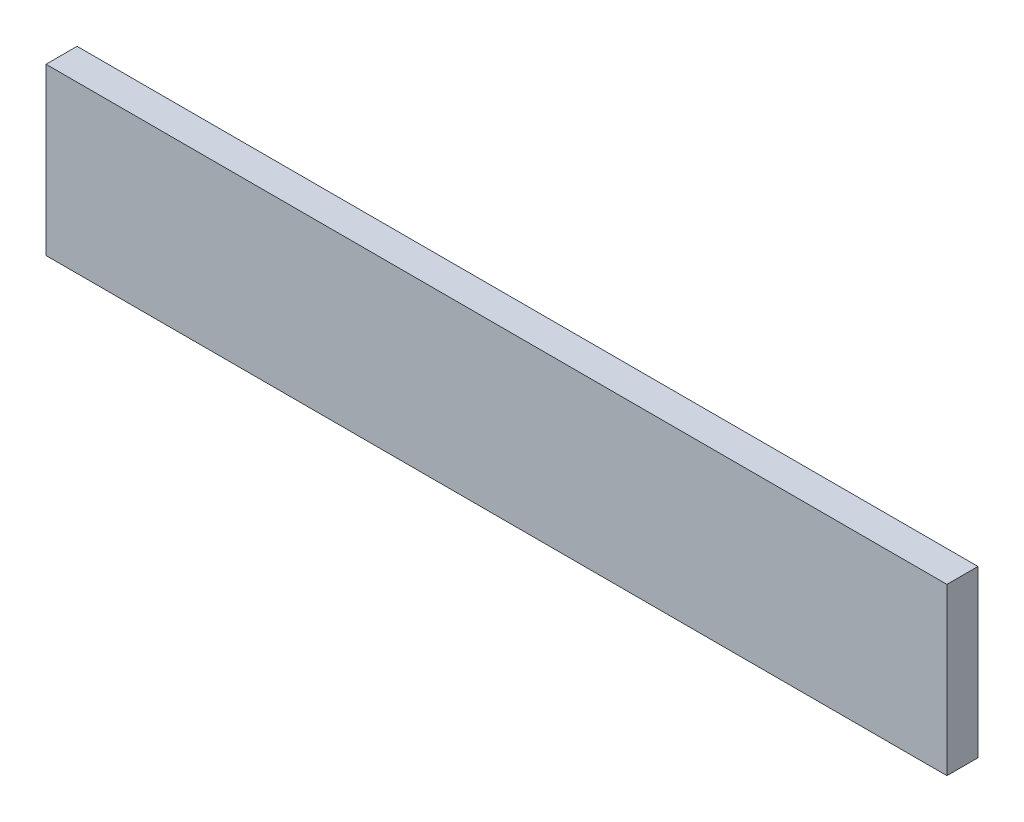
SolidWorks part; units mm, degrees
material "Pine"
ref_plane "Front Plane" through (0, 0, 0) normal (0, 0, 1) x (1, 0, 0)
ref_plane "Top Plane" through (0, 0, 0) normal (0, 1, 0) x (1, 0, 0)
ref_plane "Right Plane" through (0, 0, 0) normal (1, 0, 0) x (0, 0, -1)
sketch "Sketch1" plane through (0, 0, 0) normal (0, 0, 1) x (1, 0, 0)
  line L1 (-276.225, -50.8) -> (276.225, -50.8)
  line L2 (-276.225, -50.8) -> (-276.225, 50.8)
  line L3 (-276.225, 50.8) -> (276.225, 50.8)
  line L4 (276.225, -50.8) -> (276.225, 50.8)
  line L5 (-276.225, -50.8) -> (276.225, 50.8) construction
  line L6 (-276.225, 50.8) -> (276.225, -50.8) construction
  point P0 (0, 0)
  dimension "D1" = 552.45
  dimension "D2" = 101.6
extrude "Boss-Extrude1" add sketch "Sketch1" along normal blind 19.05
